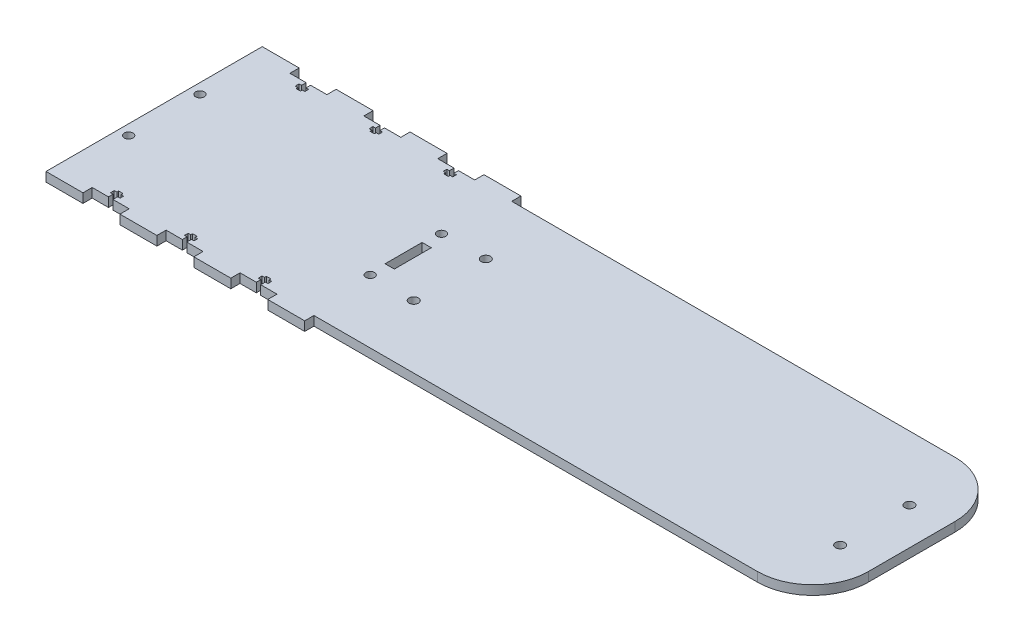
SolidWorks part; units mm, degrees
material "6061 Alloy"
ref_plane "Front Plane" through (0, 0, 0) normal (0, 0, 1) x (1, 0, 0)
ref_plane "Top Plane" through (0, 0, 0) normal (0, 1, 0) x (1, 0, 0)
ref_plane "Right Plane" through (0, 0, 0) normal (1, 0, 0) x (0, 0, -1)
sketch "Sketch1" plane through (0, 0, 0) normal (0, 1, 0) x (1, 0, 0)
  line L0 (-254.4303, 52.1591) -> (-254.4303, -83.7309)
  line L1 (-229.0303, 52.1591) -> (-217.8542, 52.1591)
  line L2 (-229.0303, -83.7309) -> (-217.8542, -83.7309)
  line L3 (-254.4303, 52.1591) -> (-254.4303, 58.5091)
  line L4 (-254.4303, 58.5091) -> (-229.0303, 58.5091)
  line L5 (-229.0303, 58.5091) -> (-229.0303, 52.1591)
  line L6 (-203.6303, 52.1591) -> (-203.6303, 58.5091)
  line L7 (-203.6303, 58.5091) -> (-178.2303, 58.5091)
  line L8 (-178.2303, 58.5091) -> (-178.2303, 52.1591)
  line L9 (-152.8303, 52.1591) -> (-152.8303, 58.5091)
  line L10 (-152.8303, 58.5091) -> (-127.4303, 58.5091)
  line L11 (-127.4303, 58.5091) -> (-127.4303, 52.1591)
  line L12 (-102.0303, 52.1591) -> (-102.0303, 58.5091)
  line L13 (-102.0303, 58.5091) -> (-76.6303, 58.5091)
  line L14 (-76.6303, 58.5091) -> (-76.6303, 52.1591)
  line L15 (-178.2303, 52.1591) -> (-167.0542, 52.1591)
  line L16 (-127.4303, 52.1591) -> (-116.2542, 52.1591)
  line L17 (-254.4303, -83.7309) -> (-254.4303, -90.0809)
  line L18 (-254.4303, -90.0809) -> (-229.0303, -90.0809)
  line L19 (-229.0303, -90.0809) -> (-229.0303, -83.7309)
  line L20 (-203.6303, -83.7309) -> (-203.6303, -90.0809)
  line L21 (-203.6303, -90.0809) -> (-178.2303, -90.0809)
  line L22 (-178.2303, -90.0809) -> (-178.2303, -83.7309)
  line L23 (-152.8303, -83.7309) -> (-152.8303, -90.0809)
  line L24 (-152.8303, -90.0809) -> (-127.4303, -90.0809)
  line L25 (-127.4303, -90.0809) -> (-127.4303, -83.7309)
  line L26 (-102.0303, -83.7309) -> (-102.0303, -90.0809)
  line L27 (-102.0303, -90.0809) -> (-76.6303, -90.0809)
  line L28 (-76.6303, -90.0809) -> (-76.6303, -83.7309)
  line L29 (-178.2303, -83.7309) -> (-167.0542, -83.7309)
  line L30 (-127.4303, -83.7309) -> (-116.2542, -83.7309)
  line L31 (-214.8063, -76.7459) -> (-214.8063, -78.0159)
  line L32 (-214.8063, -78.0159) -> (-213.0537, -78.0159)
  line L33 (-213.0537, -78.0159) -> (-213.0537, -80.5559)
  line L34 (-213.0537, -80.5559) -> (-214.8063, -80.5559)
  line L35 (-214.8063, -80.5559) -> (-214.8063, -83.7309)
  line L36 (-217.8542, -76.7459) -> (-217.8542, -78.0159)
  line L37 (-217.8542, -78.0159) -> (-219.6068, -78.0159)
  line L38 (-219.6068, -78.0159) -> (-219.6068, -80.5559)
  line L39 (-219.6068, -80.5559) -> (-217.8542, -80.5559)
  line L40 (-217.8542, -80.5559) -> (-217.8542, -83.7309)
  line L41 (-214.8063, 45.1741) -> (-214.8063, 46.4441)
  line L42 (-214.8063, 46.4441) -> (-213.0537, 46.4441)
  line L43 (-213.0537, 46.4441) -> (-213.0537, 48.9841)
  line L44 (-213.0537, 48.9841) -> (-214.8063, 48.9841)
  line L45 (-214.8063, 48.9841) -> (-214.8063, 52.1591)
  line L46 (-217.8542, 45.1741) -> (-217.8542, 46.4441)
  line L47 (-217.8542, 46.4441) -> (-219.6068, 46.4441)
  line L48 (-219.6068, 46.4441) -> (-219.6068, 48.9841)
  line L49 (-219.6068, 48.9841) -> (-217.8542, 48.9841)
  line L50 (-217.8542, 48.9841) -> (-217.8542, 52.1591)
  line L51 (-164.0063, 45.1741) -> (-164.0063, 46.4441)
  line L52 (-164.0063, 46.4441) -> (-162.2537, 46.4441)
  line L53 (-162.2537, 46.4441) -> (-162.2537, 48.9841)
  line L54 (-162.2537, 48.9841) -> (-164.0063, 48.9841)
  line L55 (-164.0063, 48.9841) -> (-164.0063, 52.1591)
  line L56 (-167.0542, 45.1741) -> (-167.0542, 46.4441)
  line L57 (-167.0542, 46.4441) -> (-168.8068, 46.4441)
  line L58 (-168.8068, 46.4441) -> (-168.8068, 48.9841)
  line L59 (-168.8068, 48.9841) -> (-167.0542, 48.9841)
  line L60 (-167.0542, 48.9841) -> (-167.0542, 52.1591)
  line L61 (-113.2063, 45.1741) -> (-113.2063, 46.4441)
  line L62 (-113.2063, 46.4441) -> (-111.4537, 46.4441)
  line L63 (-111.4537, 46.4441) -> (-111.4537, 48.9841)
  line L64 (-111.4537, 48.9841) -> (-113.2063, 48.9841)
  line L65 (-113.2063, 48.9841) -> (-113.2063, 52.1591)
  line L66 (-116.2542, 45.1741) -> (-116.2542, 46.4441)
  line L67 (-116.2542, 46.4441) -> (-118.0068, 46.4441)
  line L68 (-118.0068, 46.4441) -> (-118.0068, 48.9841)
  line L69 (-118.0068, 48.9841) -> (-116.2542, 48.9841)
  line L70 (-116.2542, 48.9841) -> (-116.2542, 52.1591)
  line L71 (-164.0063, -76.7459) -> (-164.0063, -78.0159)
  line L72 (-164.0063, -78.0159) -> (-162.2537, -78.0159)
  line L73 (-162.2537, -78.0159) -> (-162.2537, -80.5559)
  line L74 (-162.2537, -80.5559) -> (-164.0063, -80.5559)
  line L75 (-164.0063, -80.5559) -> (-164.0063, -83.7309)
  line L76 (-167.0542, -76.7459) -> (-167.0542, -78.0159)
  line L77 (-167.0542, -78.0159) -> (-168.8068, -78.0159)
  line L78 (-168.8068, -78.0159) -> (-168.8068, -80.5559)
  line L79 (-168.8068, -80.5559) -> (-167.0542, -80.5559)
  line L80 (-167.0542, -80.5559) -> (-167.0542, -83.7309)
  line L81 (-113.2063, -76.7459) -> (-113.2063, -78.0159)
  line L82 (-113.2063, -78.0159) -> (-111.4537, -78.0159)
  line L83 (-111.4537, -78.0159) -> (-111.4537, -80.5559)
  line L84 (-111.4537, -80.5559) -> (-113.2063, -80.5559)
  line L85 (-113.2063, -80.5559) -> (-113.2063, -83.7309)
  line L86 (-116.2542, -76.7459) -> (-116.2542, -78.0159)
  line L87 (-116.2542, -78.0159) -> (-118.0068, -78.0159)
  line L88 (-118.0068, -78.0159) -> (-118.0068, -80.5559)
  line L89 (-118.0068, -80.5559) -> (-116.2542, -80.5559)
  line L90 (-116.2542, -80.5559) -> (-116.2542, -83.7309)
  line L91 (-214.8063, -83.7309) -> (-203.6303, -83.7309)
  line L92 (-164.0063, -83.7309) -> (-152.8303, -83.7309)
  line L93 (-113.2063, -83.7309) -> (-102.0303, -83.7309)
  line L94 (-214.8063, 52.1591) -> (-203.6303, 52.1591)
  line L95 (-164.0063, 52.1591) -> (-152.8303, 52.1591)
  line L96 (-113.2063, 52.1591) -> (-102.0303, 52.1591)
  line L97 (266.2697, 14.0591) -> (266.2697, -45.6309)
  line L98 (-76.6303, -83.7309) -> (228.1697, -83.7309)
  line L99 (-76.6303, -15.7859) -> (-76.6303, -3.0859)
  line L100 (-76.6303, -3.0859) -> (-82.9591, -3.0859)
  line L101 (-82.9591, -3.0859) -> (-82.9591, -28.4859)
  line L102 (-82.9591, -28.4859) -> (-76.6303, -28.4859)
  line L103 (-76.6303, -28.4859) -> (-76.6303, -15.7859)
  line L104 (-76.6303, 52.1591) -> (228.1697, 52.1591)
  line L105 (-217.8542, 45.1741) -> (-214.8063, 45.1741)
  line L106 (-167.0542, 45.1741) -> (-164.0063, 45.1741)
  line L107 (-116.2542, 45.1741) -> (-113.2063, 45.1741)
  line L108 (-217.8542, -76.7459) -> (-214.8063, -76.7459)
  line L109 (-167.0542, -76.7459) -> (-164.0063, -76.7459)
  line L110 (-116.2542, -76.7459) -> (-113.2063, -76.7459)
  arc A0 (266.2697, 14.0591) -> (228.1697, 52.1591) centre (228.1697, 14.0591) ccw
  arc A1 (228.1697, -83.7309) -> (266.2697, -45.6309) centre (228.1697, -45.6309) ccw
  circle A2 centre (240.8697, 8.0266) radius 3.175
  circle A3 centre (240.8697, -39.5984) radius 3.175
  circle A4 centre (-51.2303, -40.5509) radius 3.175
  circle A5 centre (-51.2303, 8.9791) radius 3.175
  circle A6 centre (-247.4303, 8.7141) radius 3
  circle A7 centre (-247.4303, -40.286) radius 3
  circle A8 centre (-81.4304, 8.7141) radius 3
  circle A9 centre (-81.4304, -40.286) radius 3
extrude "Boss-Extrude1" add sketch "Sketch1" along normal blind 6.35
